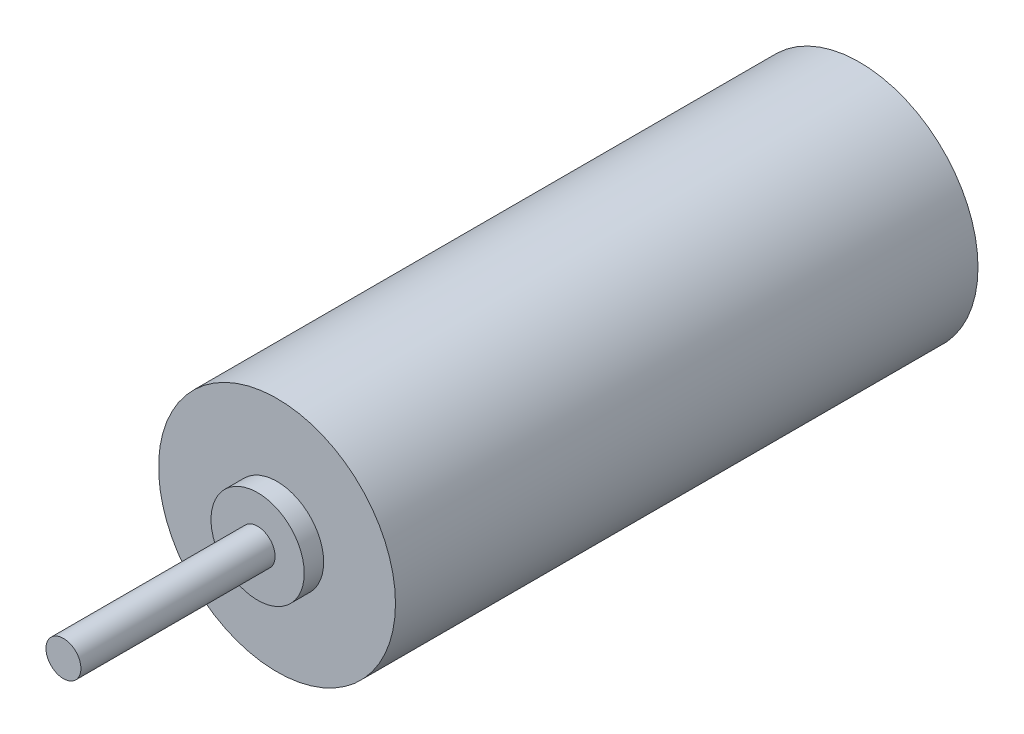
SolidWorks part; units mm, degrees
ref_plane "Ön Düzlem" through (0, 0, 0) normal (0, 0, 1) x (1, 0, 0)
ref_plane "Üst Düzlem" through (0, 0, 0) normal (0, 1, 0) x (1, 0, 0)
ref_plane "Sağ Düzlem" through (0, 0, 0) normal (1, 0, 0) x (0, 0, -1)
sketch "Sketch1" plane through (0, 0, 0) normal (0, 0, 1) x (1, 0, 0)
  circle A0 centre (0, 0) radius 3.05
  dimension "D1" = 6.1
extrude "Boss-Extrude1" add sketch "Sketch1" along normal blind 15
sketch "Sketch2" plane through (0, 0, 15) normal (0, 0, 1) x (1, 0, 0)
  circle A0 centre (0, 0) radius 1.2
  dimension "D1" = 2.4
extrude "Boss-Extrude2" add sketch "Sketch2" along normal blind 0.5
sketch "Sketch3" plane through (0, 0, 15.5) normal (0, 0, 1) x (1, 0, 0)
  circle A0 centre (0, 0) radius 0.45
  dimension "D1" = 0.9
extrude "Boss-Extrude3" add sketch "Sketch3" along normal blind 5
